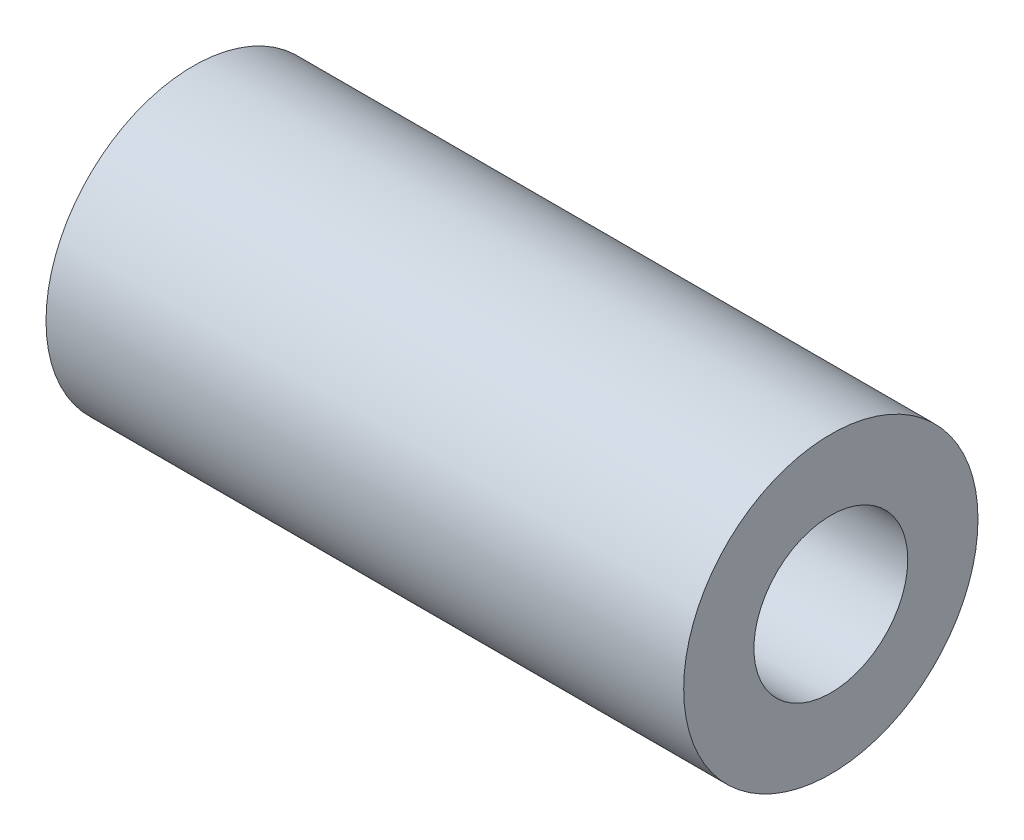
SolidWorks part; units mm, degrees
material "6061-T6 (SS)"
ref_plane "Front Plane" through (0, 0, 0) normal (0, 0, 1) x (1, 0, 0)
ref_plane "Top Plane" through (0, 0, 0) normal (0, 1, 0) x (1, 0, 0)
ref_plane "Right Plane" through (0, 0, 0) normal (1, 0, 0) x (0, 0, -1)
sketch "Sketch1" plane through (0, 0, 0) normal (1, 0, 0) x (0, 0, -1)
  circle A0 centre (0, 0) radius 4.7625
  circle A1 centre (0, 0) radius 2.4892
  dimension "D1" = 4.9784
  dimension "D2" = 9.525
extrude "Boss-Extrude1" add sketch "Sketch1" along normal mid plane 20.6375
